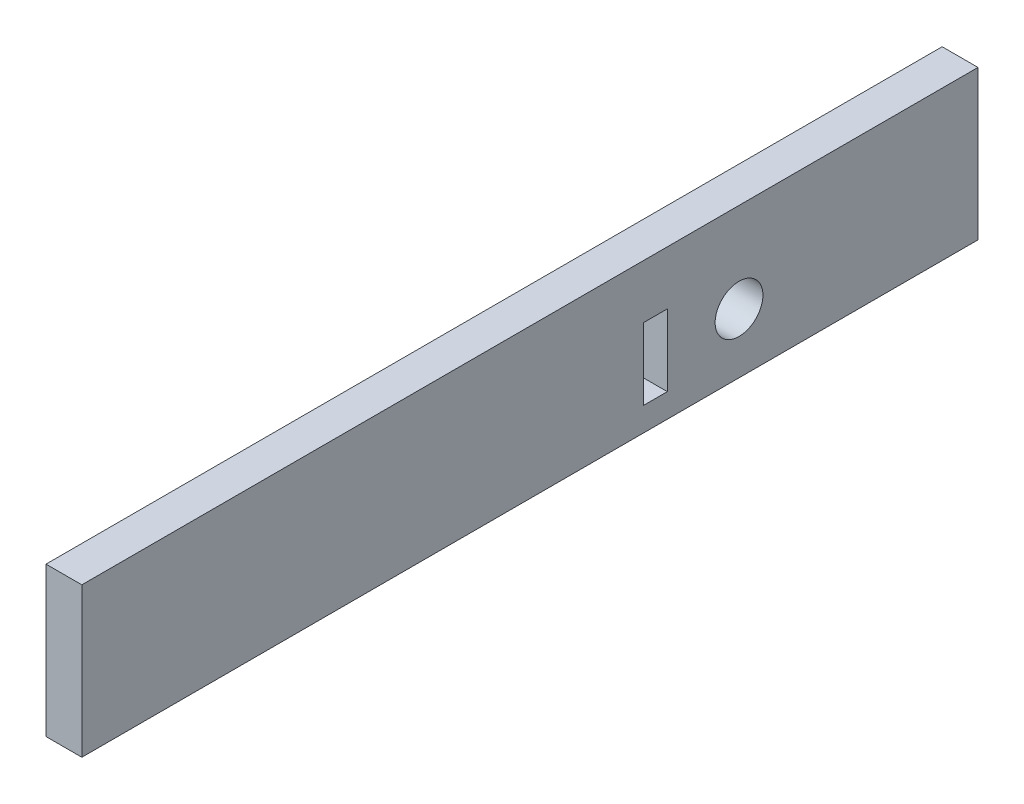
SolidWorks part; units mm, degrees
material "6061-T6 (SS)"
ref_plane "Front Plane" through (0, 0, 0) normal (0, 0, 1) x (1, 0, 0)
ref_plane "Top Plane" through (0, 0, 0) normal (0, 1, 0) x (1, 0, 0)
ref_plane "Right Plane" through (0, 0, 0) normal (1, 0, 0) x (0, 0, -1)
sketch "Sketch1" plane through (0, 0, 0) normal (1, 0, 0) x (0, 0, -1)
  line L0 (110, 10) -> (80.5148, 10) construction
  line L1 (0, 0) -> (150, 0)
  line L2 (0, 0) -> (0, 25)
  line L3 (0, 25) -> (150, 25)
  line L4 (150, 0) -> (150, 25)
  line L5 (94, 16) -> (98, 16)
  line L6 (94, 16) -> (94, 4)
  line L7 (94, 4) -> (98, 4)
  line L8 (98, 16) -> (98, 4)
  circle A0 centre (110, 10) radius 4
  point P11 (98, 10)
  dimension "D3" = 8
  dimension "D8" = 12
  dimension "D1" = 150
  dimension "D2" = 25
  dimension "D4" = 10
  dimension "D5" = 40
  dimension "D6" = 4
  dimension "D7" = 12
extrude "Boss-Extrude1" add sketch "Sketch1" along normal blind 6
